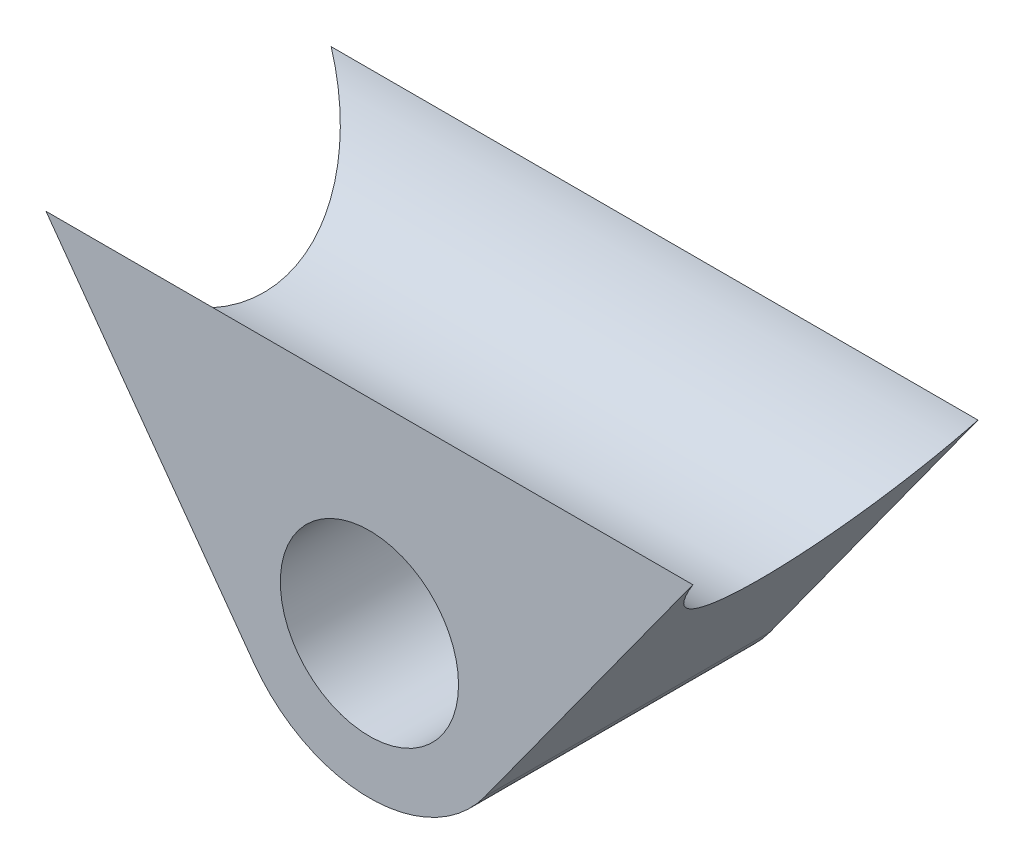
SolidWorks part; units mm, degrees
ref_plane "Front" through (0, 0, 0) normal (0, 0, 1) x (1, 0, 0)
ref_plane "Top" through (0, 0, 0) normal (0, 1, 0) x (1, 0, 0)
ref_plane "Right" through (0, 0, 0) normal (1, 0, 0) x (0, 0, -1)
sketch "Sketch1" plane through (0, 0, 0) normal (0, 0, 1) x (1, 0, 0)
  line L0 (-10.2902, -7.4432) -> (-31.75, 22.225)
  line L1 (-31.75, 22.225) -> (31.75, 22.225)
  line L2 (31.75, 22.225) -> (10.2902, -7.4432)
  circle A0 centre (0, 0) radius 7.9375
  arc A1 (-10.2902, -7.4432) -> (10.2902, -7.4432) centre (0, 0) ccw
  dimension "D1" = 15.875
  dimension "D2" = 12.7
  dimension "D3" = 22.225
  dimension "D4" = 63.5
extrude "Extrude1" add sketch "Sketch1" against normal blind 25.4 from offset 25.4
sketch3d "3DSketch1"
  line L0 (0, 0, 0) -> (0, 0, 25.4) construction
  line L1 (0, 0, 0) -> (0, 0, 25.4) construction
  point P0 (0, 0, 25.4)
  point P1 (0, 0, 0)
  point P7 (0, 0, 12.7)
sketch "Sketch2" plane through (0, 0, 0) normal (1, 0, 0) x (0, 0, -1)
  line L1 (0, 22.225) -> (0, -7.4432) construction
  line L2 (0, 22.225) -> (-25.4, 22.225) construction
  circle A0 centre (-12.7, 22.225) radius 13.335
  dimension "D1" = 26.67
  dimension "D2" = 12.7
extrude "Extrude3" cut sketch "Sketch2" against normal mid plane 146.05
